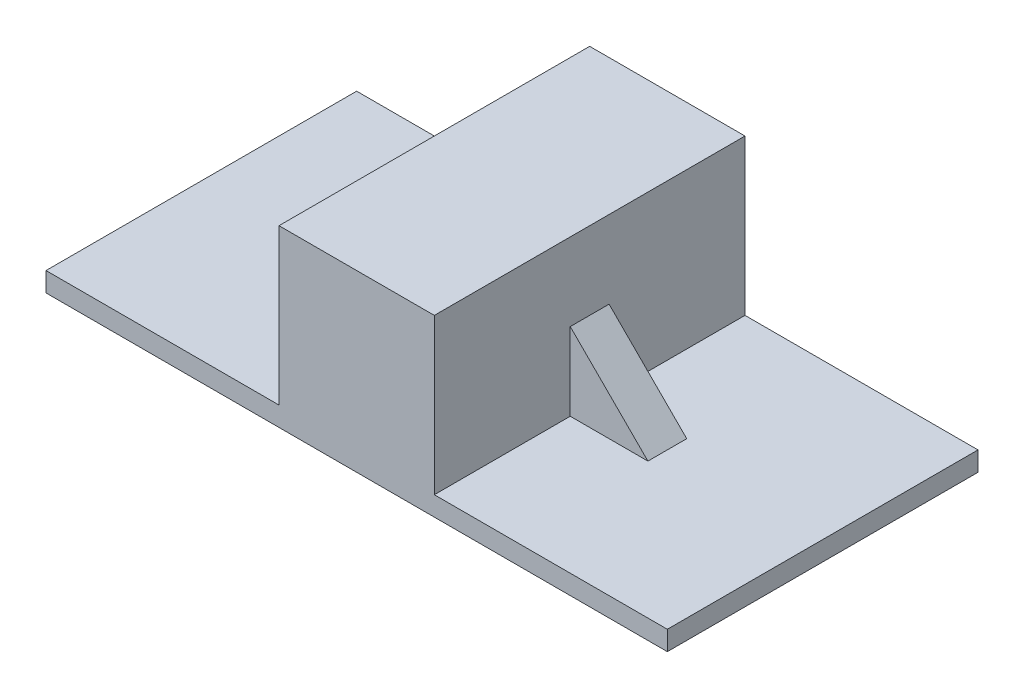
SolidWorks part; units mm, degrees
ref_plane "Front Plane" through (0, 0, 0) normal (0, 0, 1) x (1, 0, 0)
ref_plane "Top Plane" through (0, 0, 0) normal (0, 1, 0) x (1, 0, 0)
ref_plane "Right Plane" through (0, 0, 0) normal (1, 0, 0) x (0, 0, -1)
sketch "Sketch1" plane through (0, 0, 0) normal (0, 1, 0) x (1, 0, 0)
  line L1 (0, 0) -> (203.2, 0)
  line L2 (0, 0) -> (0, 101.6)
  line L3 (0, 101.6) -> (203.2, 101.6)
  line L4 (203.2, 0) -> (203.2, 101.6)
  dimension "D1" = 203.2
  dimension "D2" = 101.6
extrude "Boss-Extrude2" add sketch "Sketch1" along normal blind 6.35
sketch "Sketch3" plane through (0, 6.35, 0) normal (0, 1, 0) x (1, 0, 0)
  line L0 (203.2, 101.6) -> (0, 101.6) construction
  line L1 (76.2, 101.6) -> (127, 101.6)
  line L2 (76.2, 101.6) -> (76.2, 0)
  line L3 (76.2, 0) -> (127, 0)
  line L4 (127, 101.6) -> (127, 0)
  line L5 (0, 0) -> (203.2, 0) construction
  line L6 (203.2, 0) -> (203.2, 101.6) construction
  dimension "D1" = 50.8
  dimension "D2" = 76.2
extrude "Boss-Extrude3" add sketch "Sketch3" along normal blind 50.8 contours L2 L1 L4 L3
ref_plane "Plane1" through (0, 0, -50.8) normal (0, 0, 1) x (1, 0, 0)
sketch "Sketch4" plane through (0, 0, -50.8) normal (0, 0, 1) x (1, 0, 0)
  line L0 (127, 31.75) -> (152.4, 6.35)
  line L1 (127, 57.15) -> (127, 6.35) construction
  line L2 (127, 6.35) -> (203.2, 6.35) construction
  line L3 (76.2, 57.15) -> (76.2, 6.35) construction
  line L4 (76.2, 31.75) -> (50.8, 6.35)
  line L5 (0, 6.35) -> (76.2, 6.35) construction
  line L6 (76.2, 31.75) -> (76.2, 6.35)
  line L7 (76.2, 6.35) -> (50.8, 6.35)
  line L8 (127, 31.75) -> (127, 6.35)
  line L9 (127, 6.35) -> (152.4, 6.35)
  dimension "D1" = 25.4
  dimension "D2" = 25.4
  dimension "D3" = 25.4
  dimension "D4" = 25.4
extrude "Boss-Extrude4" add sketch "Sketch4" along normal mid plane 12.7
